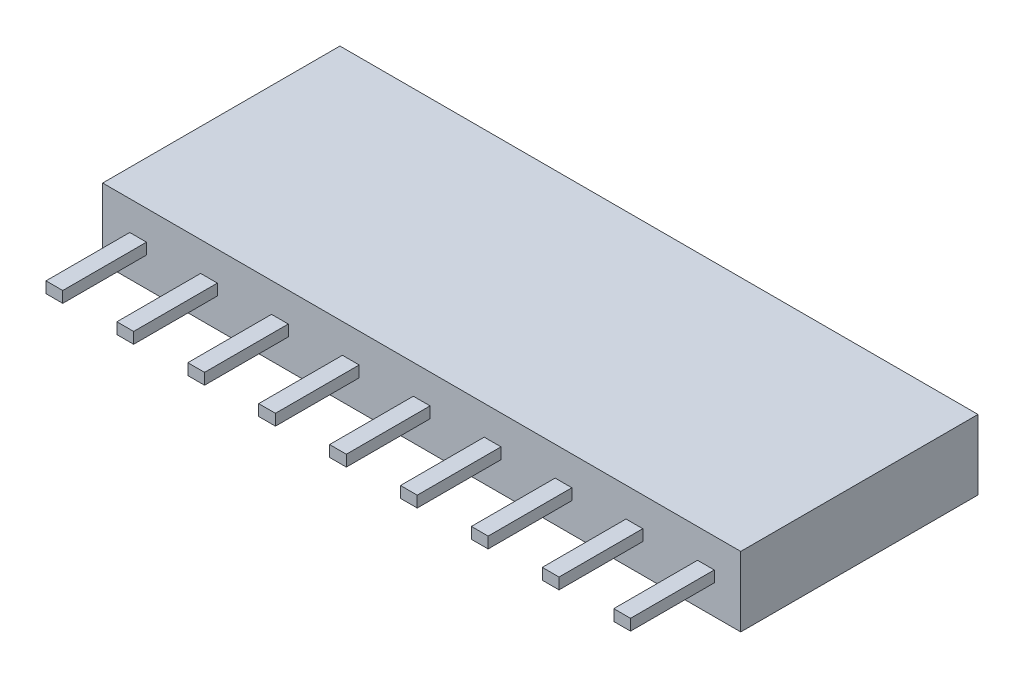
SolidWorks part; units mm, degrees
ref_plane "Front" through (0, 0, 0) normal (0, 0, 1) x (1, 0, 0)
ref_plane "Top" through (0, 0, 0) normal (0, 1, 0) x (1, 0, 0)
ref_plane "Right" through (0, 0, 0) normal (1, 0, 0) x (0, 0, -1)
sketch "Эскиз1" plane through (0, 0, 0) normal (0, 1, 0) x (1, 0, 0)
  line L1 (-11.43, 4.25) -> (11.43, 4.25)
  line L2 (-11.43, 4.25) -> (-11.43, -4.25)
  line L3 (-11.43, -4.25) -> (11.43, -4.25)
  line L4 (11.43, 4.25) -> (11.43, -4.25)
  line L5 (-11.43, 4.25) -> (11.43, -4.25) construction
  line L6 (-11.43, -4.25) -> (11.43, 4.25) construction
  point P0 (0, 0)
extrude "Бобышка-Вытянуть1" add sketch "Эскиз1" along normal blind 2.5
sketch "Эскиз2" plane through (0, 0, 4.25) normal (0, 0, 1) x (1, 0, 0)
  line L0 (-11.43, 1.25) -> (11.43, 1.25) construction
  line L1 (-11.43, 2.5) -> (-11.43, 0) construction
  line L2 (11.43, 2.5) -> (11.43, 0) construction
  line L3 (-7.92, 1.05) -> (-7.32, 1.05)
  line L4 (-10.46, 1.05) -> (-9.86, 1.05)
  line L5 (-10.46, 1.05) -> (-10.46, 1.45)
  line L6 (-10.46, 1.45) -> (-9.86, 1.45)
  line L7 (-9.86, 1.05) -> (-9.86, 1.45)
  line L8 (-10.46, 1.05) -> (-9.86, 1.45) construction
  line L9 (-10.46, 1.45) -> (-9.86, 1.05) construction
  line L10 (-7.92, 1.05) -> (-7.32, 1.45) construction
  line L11 (-7.92, 1.05) -> (-7.92, 1.45)
  line L12 (-7.92, 1.45) -> (-7.32, 1.45)
  line L13 (-7.92, 1.45) -> (-7.32, 1.05) construction
  line L14 (-7.32, 1.05) -> (-7.32, 1.45)
  line L15 (-5.38, 1.05) -> (-4.78, 1.05)
  line L16 (-5.38, 1.05) -> (-4.78, 1.45) construction
  line L17 (-5.38, 1.05) -> (-5.38, 1.45)
  line L18 (-5.38, 1.45) -> (-4.78, 1.45)
  line L19 (-5.38, 1.45) -> (-4.78, 1.05) construction
  line L20 (-4.78, 1.05) -> (-4.78, 1.45)
  line L21 (-2.84, 1.05) -> (-2.24, 1.05)
  line L22 (-2.84, 1.05) -> (-2.24, 1.45) construction
  line L23 (-2.84, 1.05) -> (-2.84, 1.45)
  line L24 (-2.84, 1.45) -> (-2.24, 1.45)
  line L25 (-2.84, 1.45) -> (-2.24, 1.05) construction
  line L26 (-2.24, 1.05) -> (-2.24, 1.45)
  line L27 (-0.3, 1.05) -> (0.3, 1.05)
  line L28 (-0.3, 1.05) -> (0.3, 1.45) construction
  line L29 (-0.3, 1.05) -> (-0.3, 1.45)
  line L30 (-0.3, 1.45) -> (0.3, 1.45)
  line L31 (-0.3, 1.45) -> (0.3, 1.05) construction
  line L32 (0.3, 1.05) -> (0.3, 1.45)
  line L33 (2.24, 1.05) -> (2.84, 1.05)
  line L34 (2.24, 1.05) -> (2.84, 1.45) construction
  line L35 (2.24, 1.05) -> (2.24, 1.45)
  line L36 (2.24, 1.45) -> (2.84, 1.45)
  line L37 (2.24, 1.45) -> (2.84, 1.05) construction
  line L38 (2.84, 1.05) -> (2.84, 1.45)
  line L39 (4.78, 1.05) -> (5.38, 1.05)
  line L40 (4.78, 1.05) -> (5.38, 1.45) construction
  line L41 (4.78, 1.05) -> (4.78, 1.45)
  line L42 (4.78, 1.45) -> (5.38, 1.45)
  line L43 (4.78, 1.45) -> (5.38, 1.05) construction
  line L44 (5.38, 1.05) -> (5.38, 1.45)
  line L45 (7.32, 1.05) -> (7.92, 1.05)
  line L46 (7.32, 1.05) -> (7.92, 1.45) construction
  line L47 (7.32, 1.05) -> (7.32, 1.45)
  line L48 (7.32, 1.45) -> (7.92, 1.45)
  line L49 (7.32, 1.45) -> (7.92, 1.05) construction
  line L50 (7.92, 1.05) -> (7.92, 1.45)
  line L51 (9.881, 1.45) -> (10.481, 1.05) construction
  line L52 (9.881, 1.45) -> (10.481, 1.45)
  line L53 (10.481, 1.05) -> (10.481, 1.45)
  line L54 (9.881, 1.05) -> (9.881, 1.45)
  line L55 (9.881, 1.05) -> (10.481, 1.45) construction
  line L56 (9.881, 1.05) -> (10.481, 1.05)
  dimension "D1" = 8
extrude "Бобышка-Вытянуть2" add sketch "Эскиз2" along normal blind 3
